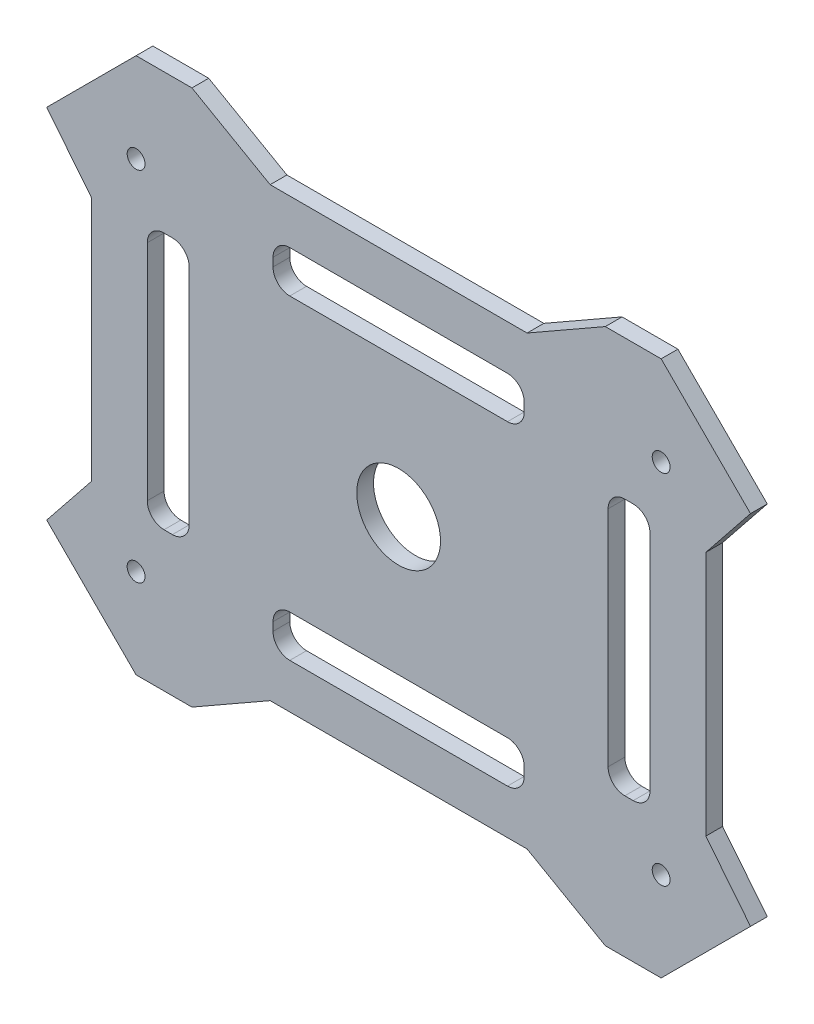
SolidWorks part; units mm, degrees
ref_plane "Front Plane" through (0, 0, 0) normal (0, 0, 1) x (1, 0, 0)
ref_plane "Top Plane" through (0, 0, 0) normal (0, 1, 0) x (1, 0, 0)
ref_plane "Right Plane" through (0, 0, 0) normal (1, 0, 0) x (0, 0, -1)
sketch "Sketch1" plane through (0, 0, 0) normal (0, 0, 1) x (1, 0, 0)
  line L0 (-135.6874, 49.993) -> (-119.6874, 65.993)
  line L1 (-95.6874, 57.993) -> (-49.6874, 57.993)
  line L2 (-17.6874, 39.993) -> (-17.6874, -4.007)
  line L3 (-135.6874, -14.007) -> (-127.6874, -4.007)
  line L4 (-109.6874, 65.993) -> (-95.6874, 57.993)
  line L5 (-119.6874, 65.993) -> (-109.6874, 65.993)
  line L6 (-25.6874, 65.993) -> (-9.6874, 49.993)
  line L7 (-135.6874, -14.007) -> (-119.6874, -30.007)
  line L8 (-119.6874, -30.007) -> (-109.6874, -30.007)
  line L9 (-25.6874, -30.007) -> (-9.6874, -14.007)
  line L10 (-35.6874, -30.007) -> (-25.6874, -30.007)
  line L11 (-35.6874, 65.993) -> (-25.6874, 65.993)
  line L12 (-127.6874, 39.993) -> (-135.6874, 49.993)
  line L14 (-49.6874, -22.007) -> (-95.6874, -22.007)
  line L15 (-17.6874, 39.993) -> (-9.6874, 49.993)
  line L16 (-17.6874, -4.007) -> (-9.6874, -14.007)
  line L17 (-49.6874, 57.993) -> (-35.6874, 65.993)
  line L18 (-95.6874, -22.007) -> (-109.6874, -30.007)
  line L19 (-49.6874, -22.007) -> (-35.6874, -30.007)
  line L20 (-114.6874, 40.993) -> (-113.1874, 40.993)
  line L21 (-117.6874, 37.993) -> (-117.6874, -2.007)
  line L22 (-114.6874, -5.007) -> (-113.1874, -5.007)
  line L23 (-110.1874, 37.993) -> (-110.1874, -2.007)
  line L32 (-53.2005, -14.007) -> (-92.1742, -14.007)
  line L33 (-50.2005, -11.007) -> (-50.2005, -9.507)
  line L34 (-53.2005, -6.507) -> (-92.1742, -6.507)
  line L35 (-95.1742, -11.007) -> (-95.1742, -9.507)
  line L36 (-127.6874, 39.993) -> (-127.6874, -4.007)
  line L37 (-119.6874, 49.993) -> (-25.6874, 49.993) construction
  line L38 (-25.6874, 49.993) -> (-25.6874, -14.007) construction
  line L39 (-25.6874, -14.007) -> (-119.6874, -14.007) construction
  line L40 (-119.6874, -14.007) -> (-119.6874, 49.993) construction
  line L41 (-135.6874, 49.993) -> (-119.6874, 49.993) construction
  line L42 (-119.6874, 49.993) -> (-119.6874, 65.993) construction
  line L43 (-25.6874, 65.993) -> (-25.6874, 49.993) construction
  line L44 (-25.6874, 49.993) -> (-9.6874, 49.993) construction
  line L45 (-135.6874, -14.007) -> (-119.6874, -14.007) construction
  line L46 (-119.6874, -14.007) -> (-119.6874, -30.007) construction
  line L47 (-9.6874, -14.007) -> (-25.6874, -14.007) construction
  line L48 (-25.6874, -14.007) -> (-25.6874, -30.007) construction
  line L49 (-135.6874, 49.993) -> (-135.6874, -14.007) construction
  line L50 (-9.6874, 49.993) -> (-9.6874, -14.007) construction
  line L51 (-135.6874, 17.993) -> (-127.6874, 17.993) construction
  line L52 (-9.6874, 17.993) -> (-17.6874, 17.993) construction
  line L53 (-109.6874, 65.993) -> (-95.6874, 65.993) construction
  line L54 (-95.6874, 65.993) -> (-95.6874, 57.993) construction
  line L55 (-49.6874, 57.993) -> (-49.6874, 65.993) construction
  line L56 (-49.6874, 65.993) -> (-35.6874, 65.993) construction
  line L57 (-109.6874, -30.007) -> (-95.6874, -30.007) construction
  line L58 (-95.6874, -30.007) -> (-95.6874, -22.007) construction
  line L59 (-49.6874, -22.007) -> (-49.6874, -30.007) construction
  line L60 (-49.6874, -30.007) -> (-35.6874, -30.007) construction
  line L61 (-72.6874, -22.007) -> (-72.6874, -14.007) construction
  line L62 (-72.6874, 57.993) -> (-72.6874, 49.993) construction
  line L63 (-117.6874, 37.993) -> (-114.6874, 37.993) construction
  line L64 (-110.1874, 37.993) -> (-113.1874, 37.993) construction
  line L65 (-114.6874, 40.993) -> (-114.6874, 37.993) construction
  line L66 (-113.1874, 40.993) -> (-113.1874, 37.993) construction
  line L67 (-117.6874, -2.007) -> (-114.6874, -2.007) construction
  line L68 (-114.6874, -2.007) -> (-114.6874, -5.007) construction
  line L69 (-113.1874, -2.007) -> (-113.1874, -5.007) construction
  line L70 (-113.1874, -2.007) -> (-110.1874, -2.007) construction
  line L71 (-53.2005, -6.507) -> (-53.2005, -9.507) construction
  line L72 (-53.2005, -9.507) -> (-50.2005, -9.507) construction
  line L73 (-127.6874, 39.993) -> (-119.6874, 49.993) construction
  line L74 (-127.6874, -4.007) -> (-119.6874, -14.007) construction
  line L75 (-119.6874, 17.993) -> (-25.6874, 17.993) construction
  line L76 (-72.6874, 49.993) -> (-72.6874, 17.993) construction
  line L77 (-72.6874, 17.993) -> (-72.6874, -14.007) construction
  line L78 (-53.2005, -11.007) -> (-53.2005, -14.007) construction
  line L79 (-53.2005, -11.007) -> (-50.2005, -11.007) construction
  line L80 (-92.1742, -6.507) -> (-92.1742, -9.507) construction
  line L81 (-92.1742, -9.507) -> (-95.1742, -9.507) construction
  line L82 (-95.1742, -11.007) -> (-92.1742, -11.007) construction
  line L83 (-92.1742, -11.007) -> (-92.1742, -14.007) construction
  line L84 (-32.1874, 40.993) -> (-30.6874, 40.993)
  line L85 (-35.1874, 37.993) -> (-35.1874, -2.007)
  line L86 (-32.1874, -5.007) -> (-30.6874, -5.007)
  line L87 (-27.6874, 37.993) -> (-27.6874, -2.007)
  line L88 (-53.2005, 42.493) -> (-92.1742, 42.493)
  line L89 (-35.1874, 37.993) -> (-32.1874, 37.993) construction
  line L90 (-27.6874, 37.993) -> (-30.6874, 37.993) construction
  line L91 (-32.1874, 40.993) -> (-32.1874, 37.993) construction
  line L92 (-30.6874, 40.993) -> (-30.6874, 37.993) construction
  line L93 (-35.1874, -2.007) -> (-32.1874, -2.007) construction
  line L94 (-32.1874, -2.007) -> (-32.1874, -5.007) construction
  line L95 (-30.6874, -2.007) -> (-30.6874, -5.007) construction
  line L96 (-30.6874, -2.007) -> (-27.6874, -2.007) construction
  line L97 (-50.2005, 45.493) -> (-50.2005, 46.993)
  line L98 (-53.2005, 49.993) -> (-92.1742, 49.993)
  line L99 (-95.1742, 45.493) -> (-95.1742, 46.993)
  line L100 (-53.2005, 49.993) -> (-53.2005, 46.993) construction
  line L101 (-53.2005, 46.993) -> (-50.2005, 46.993) construction
  line L103 (-53.2005, 45.493) -> (-53.2005, 42.493) construction
  line L104 (-53.2005, 45.493) -> (-50.2005, 45.493) construction
  line L105 (-92.1742, 49.993) -> (-92.1742, 46.993) construction
  line L106 (-92.1742, 46.993) -> (-95.1742, 46.993) construction
  line L107 (-95.1742, 45.493) -> (-92.1742, 45.493) construction
  line L108 (-92.1742, 45.493) -> (-92.1742, 42.493) construction
  arc A8 (-110.1874, 37.993) -> (-113.1874, 40.993) centre (-113.1874, 37.993) ccw
  arc A9 (-114.6874, 40.993) -> (-117.6874, 37.993) centre (-114.6874, 37.993) ccw
  arc A10 (-113.1874, -5.007) -> (-110.1874, -2.007) centre (-113.1874, -2.007) ccw
  arc A11 (-117.6874, -2.007) -> (-114.6874, -5.007) centre (-114.6874, -2.007) ccw
  circle A12 centre (-72.6874, 17.993) radius 7.5
  arc A13 (-53.2005, -14.007) -> (-50.2005, -11.007) centre (-53.2005, -11.007) ccw
  arc A14 (-50.2005, -9.507) -> (-53.2005, -6.507) centre (-53.2005, -9.507) ccw
  arc A15 (-92.1742, -6.507) -> (-95.1742, -9.507) centre (-92.1742, -9.507) ccw
  arc A16 (-95.1742, -11.007) -> (-92.1742, -14.007) centre (-92.1742, -11.007) ccw
  circle A17 centre (-119.6874, 49.993) radius 1.6
  circle A18 centre (-25.6874, 49.993) radius 1.6
  circle A19 centre (-25.6874, -14.007) radius 1.6
  circle A20 centre (-119.6874, -14.007) radius 1.6
  arc A21 (-27.6874, 37.993) -> (-30.6874, 40.993) centre (-30.6874, 37.993) ccw
  arc A22 (-32.1874, 40.993) -> (-35.1874, 37.993) centre (-32.1874, 37.993) ccw
  arc A23 (-30.6874, -5.007) -> (-27.6874, -2.007) centre (-30.6874, -2.007) ccw
  arc A24 (-35.1874, -2.007) -> (-32.1874, -5.007) centre (-32.1874, -2.007) ccw
  arc A25 (-53.2005, 42.493) -> (-50.2005, 45.493) centre (-53.2005, 45.493) ccw
  arc A26 (-50.2005, 46.993) -> (-53.2005, 49.993) centre (-53.2005, 46.993) ccw
  arc A27 (-92.1742, 49.993) -> (-95.1742, 46.993) centre (-92.1742, 46.993) ccw
  arc A28 (-95.1742, 45.493) -> (-92.1742, 42.493) centre (-92.1742, 45.493) ccw
  point P2 (-72.6874, -14.007)
  point P3 (-27.6874, 17.993)
  point P5 (-117.6874, 17.993)
  point P7 (-72.6874, 49.993)
  dimension "D2" = 10
  dimension "D3" = 8
  dimension "D4" = 64
  dimension "D5" = 1.5
  dimension "D6" = 3
  dimension "D7" = 3
  dimension "D8" = 8
  dimension "D9" = 10
  dimension "D10" = 94
  dimension "D11" = 40
  dimension "D12" = 3
  dimension "D13" = 3
  dimension "D14" = 1.5
  dimension "D15" = 1.5
  dimension "D16" = 3
  dimension "D17" = 3
  dimension "D18" = 46
  dimension "D19" = 3
  dimension "D20" = 3
  dimension "D21" = 1.5
  dimension "D22" = 10
  dimension "D23" = 10
  dimension "D24" = 8
  dimension "D25" = 8
extrude "Boss-Extrude1" add sketch "Sketch1" along normal blind 3
